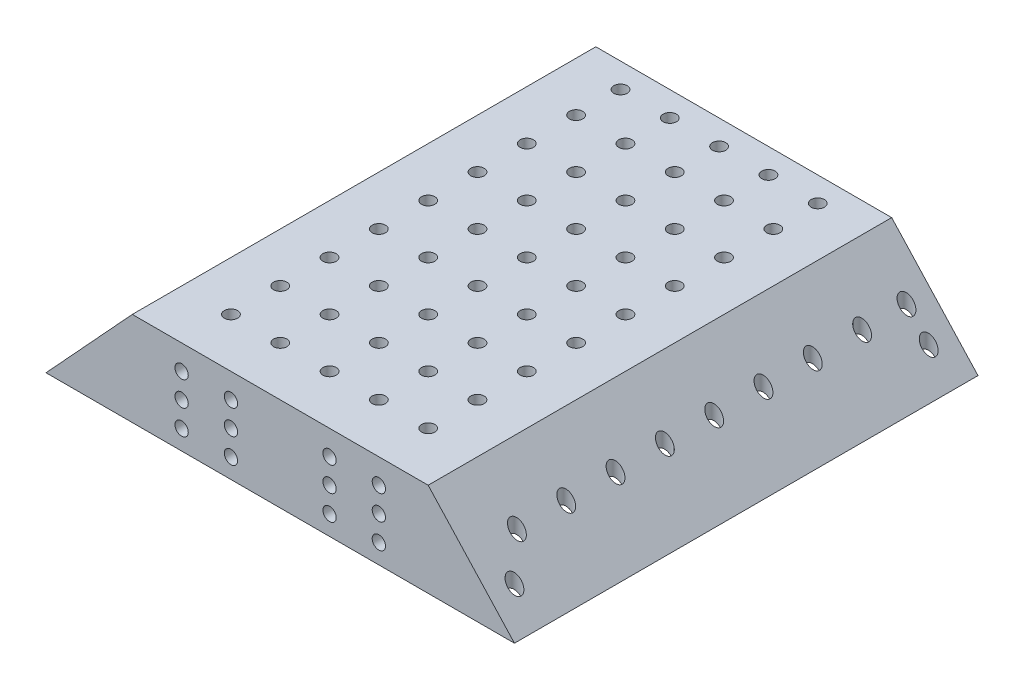
SolidWorks part; units mm, degrees
ref_plane "Alzado" through (0, 0, 0) normal (0, 0, 1) x (1, 0, 0)
ref_plane "Planta" through (0, 0, 0) normal (0, 1, 0) x (1, 0, 0)
ref_plane "Vista lateral" through (0, 0, 0) normal (1, 0, 0) x (0, 0, -1)
sketch "Croquis2" plane through (0, 0, 0) normal (0, 0, 1) x (1, 0, 0)
  line L0 (-47.5, 0) -> (-30, 0)
  line L1 (-30, 0) -> (-30, 19)
  line L2 (-30, 19) -> (-47.5, 0)
  line L3 (30, 19) -> (47.5, 0)
  line L4 (-30, 19) -> (30, 19)
  line L5 (-30, 19) -> (-30, 0)
  line L6 (-30, 0) -> (30, 0)
  line L7 (30, 19) -> (30, 0)
  line L8 (47.5, 0) -> (30, 0)
  dimension "D1" = 95
  dimension "D2" = 60
  dimension "D3" = 19
extrude "Saliente-Extruir1" add sketch "Croquis2" along normal blind 94 contours L7 L4 L1 L6 | L1 L2 L0 | L8 L3 L7
sketch "Croquis3" plane through (0, 0, 0) normal (0, 0, -1) x (-1, 0, 0)
  line L0 (-44.7368, 0) -> (-30, 16)
  line L1 (47.5, 0) -> (-47.5, 0) construction
  line L2 (-30, 16) -> (30, 16)
  line L3 (30, 16) -> (44.7368, 0)
  line L4 (44.7368, 0) -> (-44.7368, 0)
  line L5 (-30, 19) -> (-47.5, 0) construction
  line L6 (30, 19) -> (-30, 19) construction
  line L7 (30, 19) -> (47.5, 0) construction
  line L11 (47.5, 0) -> (44.7368, 0)
  line M1 (-47.5, 0) -> (47.5, 0)
  dimension "D1" = 3
extrude "Cortar-Extruir1" cut sketch "Croquis3" against normal blind 91 contours L3 L2 L0 M1
sketch "Croquis7" plane through (0, 19, 0) normal (0, 1, 0) x (1, 0, 0)
  line L0 (-47.5, -94) -> (-47.5, 0) construction
  line L1 (-47.5, 0) -> (47.5, 0) construction
  line L2 (47.5, 0) -> (47.5, -94) construction
  line L3 (47.5, -94) -> (-47.5, -94) construction
  line L4 (-42.5, 0) -> (-42.5, -94) construction
  line L5 (-47.5, -5) -> (47.5, -5) construction
  line L6 (42.5, 0) -> (42.5, -94) construction
  line L7 (-47.5, -89) -> (47.5, -89) construction
  line L8 (-47.5, -14) -> (47.5, -14) construction
  line L9 (-47.5, -24) -> (47.5, -24) construction
  line L10 (-47.5, -34) -> (47.5, -34) construction
  line L11 (-47.5, -44) -> (47.5, -44) construction
  line L12 (-47.5, -54) -> (47.5, -54) construction
  line L13 (-47.5, -64) -> (47.5, -64) construction
  line L14 (0, 0) -> (0, -94) construction
  line L15 (-47.5, -84) -> (47.5, -84) construction
  line L16 (-47.5, -74) -> (47.5, -74) construction
  line L17 (-20, 0) -> (-20, -94) construction
  line L18 (20, 0) -> (20, -94) construction
  line L19 (30, -94) -> (30, 0) construction
  line L20 (-30, -94) -> (-30, 0) construction
  line L21 (38, 0) -> (38, -94) construction
  line L22 (-38, 0) -> (-38, -94) construction
  line L23 (-10, 0) -> (-10, -94) construction
  line L24 (10, 0) -> (10, -94) construction
  dimension "D1" = 5
  dimension "D2" = 5
  dimension "D3" = 5
  dimension "D4" = 5
  dimension "D5" = 10
  dimension "D6" = 10
  dimension "D7" = 10
  dimension "D8" = 10
  dimension "D9" = 10
  dimension "D10" = 10
  dimension "D11" = 10
  dimension "D12" = 10
  dimension "D13" = 10
  dimension "D14" = 10
  dimension "D15" = 8
  dimension "D16" = 8
  dimension "D17" = 10
  dimension "D18" = 10
hole_wizard "Taladro de margen para M2.51" positions "Croquis9" profile "Croquis8" hole size "M2.5" standard "ISO" end condition through all
sketch "Croquis9" plane through (0, 19, 0) normal (0, 1, 0) x (1, 0, 0)
  line L0 (-42.5, 0) -> (-42.5, -94) construction
  line L1 (-47.5, -5) -> (47.5, -5) construction
  line L2 (42.5, 0) -> (42.5, -94) construction
  line L3 (-47.5, -89) -> (47.5, -89) construction
  line L4 (-38, 0) -> (-38, -94) construction
  line L5 (-47.5, -14) -> (47.5, -14) construction
  line L6 (-47.5, -24) -> (47.5, -24) construction
  line L7 (-47.5, -34) -> (47.5, -34) construction
  line L8 (-47.5, -44) -> (47.5, -44) construction
  line L9 (-47.5, -54) -> (47.5, -54) construction
  line L10 (-47.5, -64) -> (47.5, -64) construction
  line L11 (-47.5, -74) -> (47.5, -74) construction
  line L12 (-47.5, -84) -> (47.5, -84) construction
  line L13 (-20, 0) -> (-20, -94) construction
  line L14 (20, 0) -> (20, -94) construction
  line L15 (38, 0) -> (38, -94) construction
  line L16 (-10, 0) -> (-10, -94) construction
  line L17 (10, 0) -> (10, -94) construction
  point P0 (-42.5, -5)
  point P6 (42.5, -5)
  point P10 (42.5, -89)
  point P14 (-42.5, -89)
  point P18 (-38, -5)
  point P22 (-38, -14)
  point P26 (-38, -24)
  point P30 (-38, -34)
  point P34 (-38, -44)
  point P38 (-38, -54)
  point P42 (-38, -64)
  point P46 (-38, -74)
  point P50 (-38, -84)
  point P54 (-20, -5)
  point P58 (-20, -14)
  point P60 (-20, -24)
  point P62 (-20, -34)
  point P64 (-20, -44)
  point P66 (-20, -54)
  point P68 (-20, -64)
  point P70 (-20, -74)
  point P72 (-20, -84)
  point P74 (0, -5)
  point P76 (0, -14)
  point P78 (0, -24)
  point P80 (0, -34)
  point P82 (0, -44)
  point P84 (0, -54)
  point P86 (0, -64)
  point P88 (0, -74)
  point P90 (0, -84)
  point P92 (20, -5)
  point P96 (20, -14)
  point P98 (20, -24)
  point P100 (20, -34)
  point P102 (20, -44)
  point P104 (20, -54)
  point P106 (20, -64)
  point P108 (20, -74)
  point P110 (20, -84)
  point P112 (38, -5)
  point P116 (38, -14)
  point P118 (38, -24)
  point P120 (38, -34)
  point P122 (38, -44)
  point P124 (38, -54)
  point P126 (38, -64)
  point P128 (38, -74)
  point P130 (38, -84)
  point P134 (-10, -5)
  point P138 (-10, -14)
  point P140 (-10, -24)
  point P142 (-10, -34)
  point P144 (-10, -44)
  point P146 (-10, -54)
  point P148 (-10, -64)
  point P150 (-10, -74)
  point P152 (-10, -84)
  point P154 (10, -5)
  point P158 (10, -14)
  point P160 (10, -24)
  point P162 (10, -34)
  point P164 (10, -44)
  point P166 (10, -54)
  point P168 (10, -64)
  point P170 (10, -74)
  point P172 (10, -84)
sketch "Croquis8" plane through (-42.5, 19, 5) normal (1, 0, 0) x (0, 0, 1)
  line L0 (0, 0) -> (0, 19)
  line L1 (0, 19) -> (1.35, 19)
  line L2 (1.35, 19) -> (1.35, 0)
  line L5 (1.35, 0) -> (0, 0)
  line L11 (0, -6.35) -> (0, 107.95) construction
  dimension "Diámetro de taladro hasta el siguiente" = 2.7
  dimension "Profundidad de taladro hasta el siguiente" = 19
sketch "Croquis10" plane through (0, 0, 94) normal (0, 0, 1) x (1, 0, 0)
  line L0 (-34.6053, 14) -> (34.6053, 14) construction
  line L1 (-30, 19) -> (-47.5, 0) construction
  line L2 (30, 19) -> (47.5, 0) construction
  line L3 (-30, 19) -> (30, 19) construction
  line L4 (-39.2105, 9) -> (39.2105, 9) construction
  line L5 (0, 19) -> (0, 0) construction
  line L6 (-10, 19) -> (-10, 0) construction
  line L7 (-47.5, 0) -> (47.5, 0) construction
  line L8 (-20, 19) -> (-20, 0) construction
  line L9 (10, 19) -> (10, 0) construction
  line L10 (20, 19) -> (20, 0) construction
  line L11 (-43.85, 3.9629) -> (43.85, 3.9629) construction
  dimension "D1" = 5
  dimension "D2" = 5
  dimension "D3" = 10
  dimension "D4" = 10
  dimension "D5" = 10
  dimension "D6" = 10
hole_wizard "Taladro de margen para M2.52" positions "Croquis3D1" profile "Croquis11" hole size "M2.5" standard "ISO" end condition through all
sketch3d "Croquis3D1"
  line L0 (-34.6053, 14, 94) -> (34.6053, 14, 94) construction
  line L1 (-20, 19, 94) -> (-20, 0, 94) construction
  line L2 (-39.2105, 9, 94) -> (39.2105, 9, 94) construction
  line L3 (-43.85, 3.9629, 94) -> (43.85, 3.9629, 94) construction
  line L4 (-10, 19, 94) -> (-10, 0, 94) construction
  line L5 (10, 19, 94) -> (10, 0, 94) construction
  line L6 (20, 19, 94) -> (20, 0, 94) construction
  point P0 (-20, 14, 94)
  point P6 (-20, 9, 94)
  point P10 (-20, 3.9629, 94)
  point P14 (-10, 3.9629, 94)
  point P18 (-10, 9, 94)
  point P20 (-10, 14, 94)
  point P28 (10, 3.9629, 94)
  point P32 (10, 9, 94)
  point P34 (10, 14, 94)
  point P36 (20, 14, 94)
  point P40 (20, 9, 94)
  point P42 (20, 3.9629, 94)
sketch "Croquis11" plane through (-20, 14, 94) normal (1, 0, 0) x (0, -1, 0)
  line L0 (0, 0) -> (0, 94)
  line L1 (0, 94) -> (1.35, 94)
  line L2 (1.35, 94) -> (1.35, 0)
  line L5 (1.35, 0) -> (0, 0)
  line L11 (0, -6.35) -> (0, 107.95) construction
  dimension "Diámetro de taladro hasta el siguiente" = 2.7
  dimension "Profundidad de taladro hasta el siguiente" = 94
